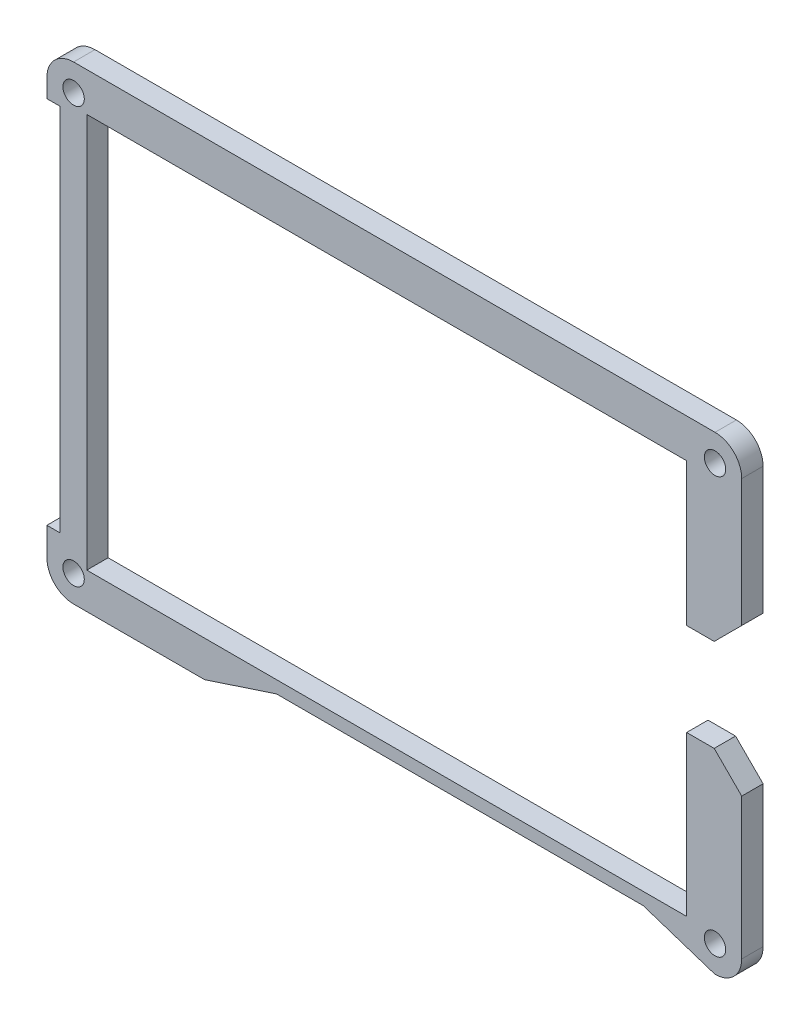
SolidWorks part; units mm, degrees
ref_plane "Front Plane" through (0, 0, 0) normal (0, 0, 1) x (1, 0, 0)
ref_plane "Top Plane" through (0, 0, 0) normal (0, 1, 0) x (1, 0, 0)
ref_plane "Right Plane" through (0, 0, 0) normal (1, 0, 0) x (0, 0, -1)
sketch "Sketch1" plane through (0, 0, 0) normal (0, 0, 1) x (1, 0, 0)
  line L0 (-401.0571, 148.341) -> (-380.1672, 148.341)
  line L1 (-399.1521, 148.341) -> (-399.1521, 95.6449)
  line L2 (-395.3675, 92.9525) -> (-395.3675, 149.2432)
  line L3 (-395.3675, 149.2432) -> (-309.8086, 149.2432)
  line L4 (-395.3675, 92.9525) -> (-309.8086, 92.9525)
  line L5 (-309.8086, 149.2432) -> (-309.8086, 92.9525)
  line L6 (-309.8086, 128.8851) -> (-321.2743, 128.8851)
  line L7 (-321.2743, 128.8851) -> (-321.2743, 115.6771)
  line L8 (-321.2743, 115.6771) -> (-309.8086, 115.6771)
  line L9 (-309.8086, 128.8851) -> (-305.8779, 128.8851)
  line L10 (-375.4172, 95.6449) -> (-401.0571, 95.6449)
  line L11 (-401.0571, 150.9566) -> (-401.0571, 148.341) construction
  line L12 (-305.7573, 154.7804) -> (-397.2471, 154.7804) construction
  line L13 (-301.9473, 91.6317) -> (-301.9473, 150.9704) construction
  line L14 (-315.9973, 91.1883) -> (-305.7573, 87.8217) construction
  line L15 (-315.9973, 91.1883) -> (-368.3165, 91.1883) construction
  line L16 (-368.3165, 91.1883) -> (-378.5565, 87.8217) construction
  line L17 (-378.5565, 87.8217) -> (-397.2472, 87.8217) construction
  line L18 (-401.0571, 95.6449) -> (-401.0571, 91.6593) construction
  line L19 (-401.0571, 150.9566) -> (-401.0571, 148.341)
  line L20 (-305.7573, 154.7804) -> (-397.2471, 154.7804)
  line L21 (-301.9473, 91.6317) -> (-301.9473, 150.9704)
  line L22 (-315.9973, 91.1883) -> (-305.7573, 87.8217)
  line L23 (-315.9973, 91.1883) -> (-368.3165, 91.1883)
  line L24 (-368.3165, 91.1883) -> (-378.5565, 87.8217)
  line L25 (-378.5565, 87.8217) -> (-397.2472, 87.8217)
  line L26 (-401.0571, 95.6449) -> (-401.0571, 91.6593)
  line L27 (-305.8779, 128.8851) -> (-301.9473, 132.8158)
  line L28 (-309.8086, 115.6771) -> (-305.8779, 115.6771)
  line L29 (-305.8779, 115.6771) -> (-301.9473, 111.7464)
  line L30 (-309.8086, 141.4927) -> (-301.9473, 141.4927) construction
  line L31 (-305.878, 141.4927) -> (-305.8779, 128.8851) construction
  arc A0 (-397.2471, 154.7804) -> (-401.0571, 150.9566) centre (-397.2471, 150.9704) ccw construction
  arc A1 (-301.9473, 150.9704) -> (-305.7573, 154.7804) centre (-305.7573, 150.9704) ccw construction
  arc A2 (-305.7573, 87.8217) -> (-301.9473, 91.6317) centre (-305.7573, 91.6317) ccw construction
  arc A3 (-401.0571, 91.6593) -> (-397.2472, 87.8217) centre (-397.2472, 91.6317) ccw construction
  arc A4 (-397.2471, 154.7804) -> (-401.0571, 150.9566) centre (-397.2471, 150.9704) ccw
  arc A5 (-301.9473, 150.9704) -> (-305.7573, 154.7804) centre (-305.7573, 150.9704) ccw
  arc A6 (-305.7573, 87.8217) -> (-301.9473, 91.6317) centre (-305.7573, 91.6317) ccw
  arc A7 (-401.0571, 91.6593) -> (-397.2472, 87.8217) centre (-397.2472, 91.6317) ccw
  circle A8 centre (-397.2471, 150.9704) radius 1.3462 construction
  circle A9 centre (-305.7573, 150.9704) radius 1.3462 construction
  circle A10 centre (-305.7573, 91.6317) radius 1.3462 construction
  circle A11 centre (-397.2472, 91.6317) radius 1.3462 construction
  circle A12 centre (-397.2471, 150.9704) radius 1.3462
  circle A13 centre (-305.7573, 150.9704) radius 1.3462
  circle A14 centre (-305.7573, 91.6317) radius 1.3462
  circle A15 centre (-397.2472, 91.6317) radius 1.3462
  dimension "D1" = 1.905
  dimension "D2" = 5.6896
  dimension "D3" = 5.5372
  dimension "D4" = 5.1308
  dimension "D5" = 7.8613
  dimension "D6" = 25.8953
  dimension "D7" = 13.208
  dimension "D8" = 11.4657
  dimension "D9" = 45
  dimension "D10" = 45
extrude "Boss-Extrude1" add sketch "Sketch1" along normal blind 3.048 contours L21 A5 L20 A4 L19 L0 L2 L3 L5 L9 L27 A13 A12 | L10 L2 L0 L1 | L26 A7 L25 L24 L23 L22 A6 L21 L29 L28 L5 L4 L2 L10 A15 A14
sketch "Sketch2" plane through (0, 0, 0) normal (0, 0, -1) x (-1, 0, 0)
  circle A0 centre (305.7573, 150.9704) radius 1.524
  circle A1 centre (305.7573, 91.6317) radius 1.524
  circle A2 centre (397.2472, 91.6317) radius 1.524
  circle A3 centre (397.2471, 150.9704) radius 1.524
  dimension "D1" = 3.048
extrude "Cut-Extrude1" cut sketch "Sketch2" against normal through all
